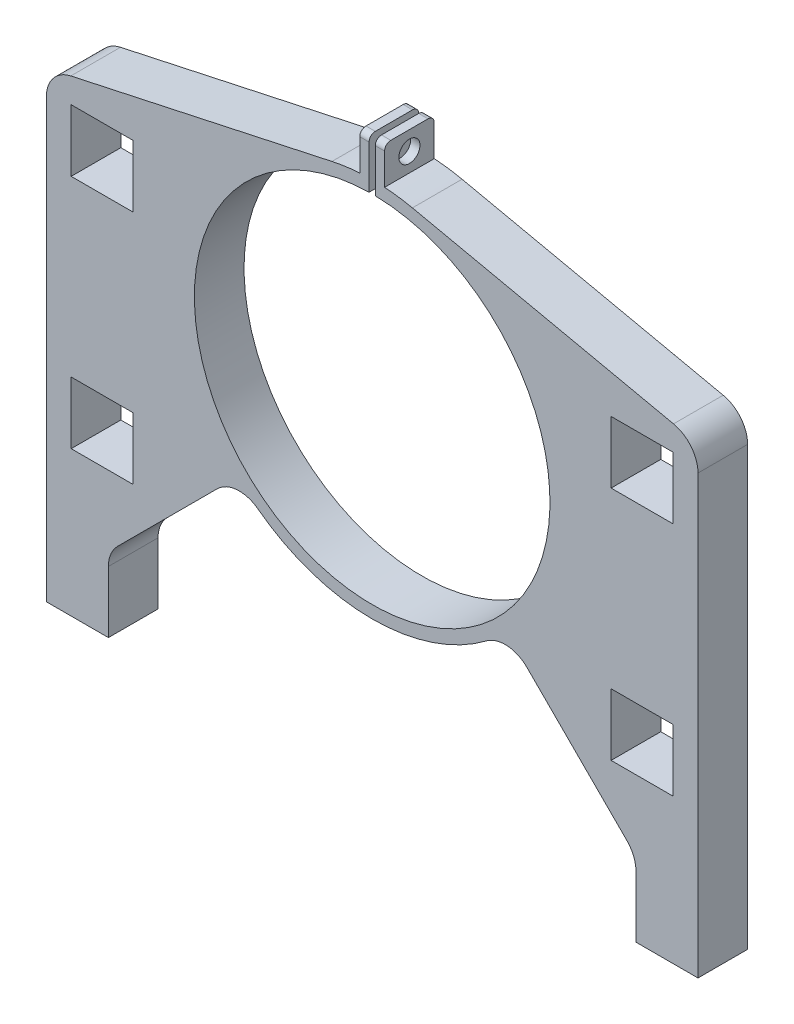
SolidWorks part; units mm, degrees
ref_plane "Ebene vorne" through (0, 0, 0) normal (0, 0, 1) x (1, 0, 0)
ref_plane "Ebene oben" through (0, 0, 0) normal (0, 1, 0) x (1, 0, 0)
ref_plane "Ebene rechts" through (0, 0, 0) normal (1, 0, 0) x (0, 0, -1)
sketch "Skizze1" plane through (0, 0, 0) normal (0, 0, 1) x (1, 0, 0)
  circle A0 centre (0, 0) radius 28.65
  circle A1 centre (0, 0) radius 30.65
  dimension "D1" = 57.3
  dimension "D2" = 2
extrude "Aufsatz-Linear austragen1" add sketch "Skizze1" along normal blind 8
sketch "Skizze2" plane through (0, 0, 8) normal (0, 0, 1) x (1, 0, 0)
  line L0 (0, 0) -> (28.5, 0) construction
  line L1 (0, 0) -> (0, 17.0738) construction
  line L2 (42.5, -42.5) -> (42.5, -54.5)
  line L3 (52.5, -54.5) -> (52.5, 20)
  line L4 (-21.6728, -21.6728) -> (-42.5, -42.5)
  line L5 (-6.4605, 29.8591) -> (-6.4816, 29.9568)
  line L6 (42.5, -54.5) -> (52.5, -54.5)
  line L7 (-21.6728, -21.6728) -> (-21.6021, -21.6021)
  line L8 (21.6728, -21.6728) -> (21.6021, -21.6021)
  line L9 (-42.5, -54.5) -> (-52.5, -54.5)
  line L10 (6.4605, 29.8591) -> (6.4816, 29.9568)
  line L11 (52.5, 20) -> (6.4816, 29.9568)
  line L12 (-52.5, -54.5) -> (-52.5, 20)
  line L13 (-42.5, -42.5) -> (-42.5, -54.5)
  line L14 (0, 0) -> (21.6728, -21.6728) construction
  line L15 (21.6728, -21.6728) -> (42.5, -42.5)
  line L27 (-52.5, 20) -> (-6.4816, 29.9568)
  circle A0 centre (0, 0) radius 30.65 construction
  arc A2 (-21.6021, -21.6021) -> (-6.4605, 29.8591) centre (0, 0) cw
  circle A3 centre (0, 0) radius 30.65 construction
  arc A4 (21.6021, -21.6021) -> (6.4605, 29.8591) centre (0, 0) ccw
  dimension "D4" = 0.1
  dimension "D1" = 85
  dimension "D2" = 10
  dimension "D3" = 20
  dimension "D5" = 12
  dimension "D6" = 45
extrude "Aufsatz-Linear austragen2" add sketch "Skizze2" against normal up to surface (8 mm away) up to face at (30.65, 0, 0)
fillet "Verrundung1" [suppressed] radius 6
sketch "Skizze3" plane through (0, 0, 8) normal (0, 0, 1) x (1, 0, 0)
  line L0 (0, 0) -> (0, 35.0949) construction
  line L1 (-0.5, 30.7687) -> (0.5, 30.7687)
  line L2 (0.5, 30.7687) -> (0.5, 27.9134)
  line L3 (0.5, 27.9134) -> (-0.5, 27.9134)
  line L4 (-0.5, 30.7687) -> (-0.5, 27.9134)
  point P8 (0, 27.9134)
  point P9 (0, 30.7687)
  dimension "D1" = 1
extrude "Schnitt-Linear austragen1" cut sketch "Skizze3" against normal blind 10
sketch "Skizze4" plane through (0, 0, 8) normal (0, 0, 1) x (1, 0, 0)
  line L0 (0.5, 30.6459) -> (0.5, 36.6459)
  line L1 (0.5, 36.6459) -> (2, 36.6459)
  line L2 (2, 36.6459) -> (2, 29.0272)
  line L3 (2, 29.0272) -> (0.5, 30.6459)
  line L4 (0, 0) -> (0, 39.0521) construction
  line L5 (-2, 29.0272) -> (-0.5, 30.6459)
  line L6 (-2, 36.6459) -> (-2, 29.0272)
  line L7 (-0.5, 36.6459) -> (-2, 36.6459)
  line L8 (-0.5, 30.6459) -> (-0.5, 36.6459)
  dimension "D1" = 1.5
  dimension "D2" = 6
extrude "Aufsatz-Linear austragen3" add sketch "Skizze4" against normal blind 8
sketch "Skizze5" plane through (-2, 0, 0) normal (-1, 0, 0) x (0, 0, 1)
  line L0 (4, 36.6459) -> (4, 30.5847) construction
  line L1 (0, 36.6459) -> (8, 36.6459) construction
  line L2 (8, 30.5847) -> (0, 30.5847) construction
  line L3 (0, 33.6153) -> (8, 33.6153) construction
  line L4 (0, 36.6459) -> (0, 30.5847) construction
  line L5 (8, 36.6459) -> (8, 30.5847) construction
  circle A0 centre (4, 33.6153) radius 2.75 construction
  circle A1 centre (4, 33.6153) radius 1.7
  dimension "D1" = 5.5
  dimension "D2" = 3.4
extrude "Schnitt-Linear austragen2" cut sketch "Skizze5" against normal blind 8
fillet "Verrundung2" radius 1 4 edges at (-1.25, 36.6459, 8) (-1.25, 36.6459, 0) (1.25, 36.6459, 8) (1.25, 36.6459, 0)
sketch "Skizze7" plane through (0, 0, 0) normal (0, 0, -1) x (-1, 0, 0)
  line L0 (-52.5, 20) -> (-52.5, -54.5) construction
  line L1 (-48.5, 6.8655) -> (-38.5, 6.8655)
  line L2 (-48.5, 6.8655) -> (-48.5, 16.8655)
  line L3 (-48.5, 16.8655) -> (-38.5, 16.8655)
  line L4 (-38.5, 6.8655) -> (-38.5, 16.8655)
  line L5 (-48.5, 6.8655) -> (-38.5, 16.8655) construction
  line L6 (-48.5, 16.8655) -> (-38.5, 6.8655) construction
  line L7 (-48.5, 16.8655) -> (-48.5, 20.8655) construction
  line L8 (-6.4816, 29.9568) -> (-52.5, 20) construction
  line L9 (-48.5, -31.1345) -> (-38.5, -31.1345)
  line L10 (-48.5, -31.1345) -> (-48.5, -21.1345)
  line L11 (-48.5, -21.1345) -> (-38.5, -21.1345)
  line L12 (-38.5, -31.1345) -> (-38.5, -21.1345)
  line L13 (-48.5, -31.1345) -> (-38.5, -21.1345) construction
  line L14 (-48.5, -21.1345) -> (-38.5, -31.1345) construction
  line L15 (0, 0) -> (0, -20.2139) construction
  line L16 (48.5, -21.1345) -> (38.5, -31.1345) construction
  line L17 (48.5, -31.1345) -> (38.5, -21.1345) construction
  line L18 (48.5, 16.8655) -> (38.5, 6.8655) construction
  line L19 (48.5, 6.8655) -> (38.5, 16.8655) construction
  line L20 (38.5, -31.1345) -> (38.5, -21.1345)
  line L21 (48.5, -21.1345) -> (38.5, -21.1345)
  line L22 (48.5, -31.1345) -> (48.5, -21.1345)
  line L23 (48.5, -31.1345) -> (38.5, -31.1345)
  line L24 (38.5, 6.8655) -> (38.5, 16.8655)
  line L25 (48.5, 16.8655) -> (38.5, 16.8655)
  line L26 (48.5, 6.8655) -> (48.5, 16.8655)
  line L27 (48.5, 6.8655) -> (38.5, 6.8655)
  line L28 (0, 0) -> (-80.5188, 0) construction
  point P0 (-43.5, 11.8655)
  point P5 (-43.5, -26.1345)
  point P26 (43.5, -26.1345)
  point P27 (43.5, 11.8655)
  dimension "D1" = 10
  dimension "D2" = 4
  dimension "D3" = 4
  dimension "D4" = 10
  dimension "D5" = 38
extrude "Schnitt-Linear austragen4" cut sketch "Skizze7" against normal blind 10
fillet "Verrundung3" radius 5 6 edges at (-42.5, -42.5, 4) (42.5, -42.5, 4) (21.6728, -21.6728, 4) (-21.6728, -21.6728, 4) (-52.5, 20, 4) (52.5, 20, 4)
